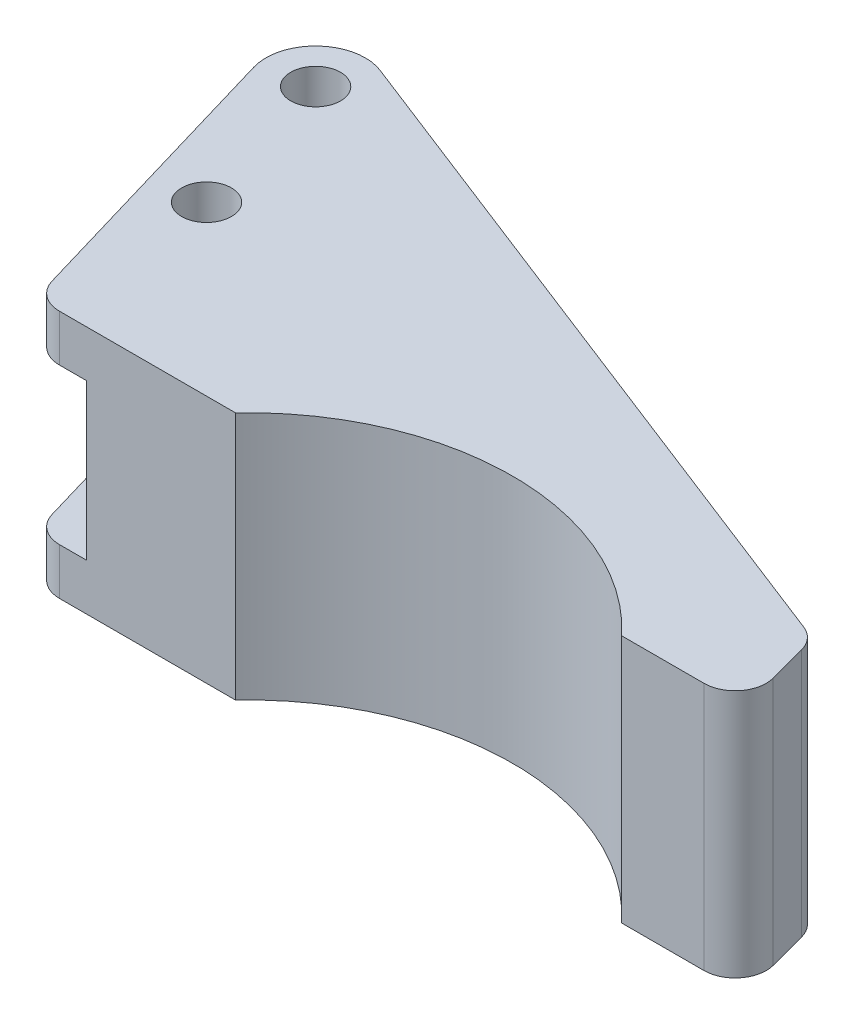
SolidWorks part; units mm, degrees
ref_plane "Front Plane" through (0, 0, 0) normal (0, 0, 1) x (1, 0, 0)
ref_plane "Top Plane" through (0, 0, 0) normal (0, 1, 0) x (1, 0, 0)
ref_plane "Right Plane" through (0, 0, 0) normal (1, 0, 0) x (0, 0, -1)
sketch "Sketch1" plane through (0, 0, 0) normal (0, 1, 0) x (1, 0, 0)
  line L0 (39.6073, 0) -> (52.8472, 0)
  line L2 (53.012, 15.859) -> (-58.5744, 59.3244)
  line L3 (-69.1516, 49.6078) -> (-55.584, 3.5861)
  line L5 (-50.7881, 0) -> (-22.4836, 0)
  line L6 (56.029, 12.4859) -> (57.679, 6.2859)
  arc A0 (-22.4836, 0) -> (39.6073, 0) centre (8.5619, -29.01) cw
  arc A1 (-55.584, 3.5861) -> (-50.7881, 0) centre (-50.7881, 5) ccw
  arc A4 (-58.5744, 59.3244) -> (-69.1516, 49.6078) centre (-61.4781, 51.87) ccw
  circle A5 centre (-61.4781, 51.87) radius 4
  circle A6 centre (-54.1481, 27) radius 4
  arc A7 (53.012, 15.859) -> (56.029, 12.4859) centre (51.1972, 11.2) cw
  arc A8 (52.8472, 0) -> (57.679, 6.2859) centre (52.8472, 5) ccw
  point P19 (59.3519, 0)
  dimension "D1" = 29.01
  dimension "D2" = 5
  dimension "D3" = 8
  dimension "D4" = 5
  dimension "D7" = 42.49
  dimension "D8" = 1.65
  dimension "D10" = 8
  dimension "D5" = 59.35
  dimension "D6" = 110.14
  dimension "D9" = 6.2
  dimension "D11" = 22
  dimension "D12" = 24.87
  dimension "D13" = 7.33
  dimension "D14" = 3.36
extrude "Boss-Extrude1" add sketch "Sketch1" along normal blind 40
sketch "Sketch2" plane through (0, 0, 0) normal (0, 0, 1) x (1, 0, 0)
  line L0 (-69.4781, 40) -> (-69.4781, 0) construction
  line L1 (-69.4781, 32.5) -> (-46.4781, 32.5)
  line L2 (-69.4781, 32.5) -> (-69.4781, 7.5)
  line L3 (-69.4781, 7.5) -> (-46.4781, 7.5)
  line L4 (-46.4781, 32.5) -> (-46.4781, 7.5)
  line L5 (-69.1516, 40) -> (-55.584, 40) construction
  dimension "D1" = 25
  dimension "D2" = 23
  dimension "D3" = 7.5
extrude "Cut-Extrude1" cut sketch "Sketch2" against normal through all
